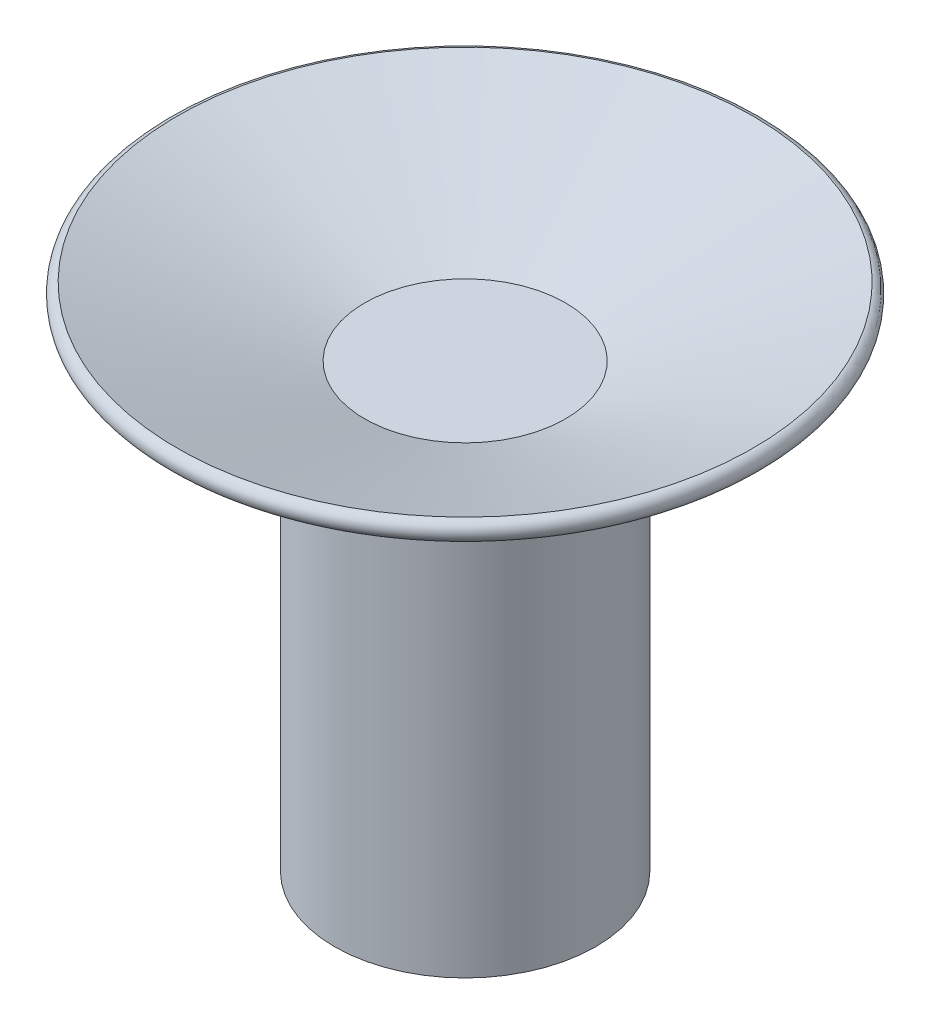
SolidWorks part; units mm, degrees
ref_plane "Plan de face" through (0, 0, 0) normal (0, 0, 1) x (1, 0, 0)
ref_plane "Plan de dessus" through (0, 0, 0) normal (0, 1, 0) x (1, 0, 0)
ref_plane "Plan de droite" through (0, 0, 0) normal (1, 0, 0) x (0, 0, -1)
sketch "Esquisse1" plane through (0, 0, 0) normal (0, 0, 1) x (1, 0, 0)
  line L0 (0, 0) -> (0, 11.1884) construction
  line L1 (0, 0) -> (5, 0)
  line L2 (5, 0) -> (14.3969, 3.4202)
  line L3 (0, 0) -> (0, 1)
  line L4 (14.3226, 4.3931) -> (5, 1)
  line L5 (5, 1) -> (0, 1)
  arc A0 (14.3969, 3.4202) -> (14.3226, 4.3931) centre (14.2237, 3.8963) ccw
  dimension "D1" = 5
  dimension "D2" = 160
  dimension "D3" = 1
  dimension "D4" = 10
revolve "Révolution1" add sketch "Esquisse1" angle 360 about L0
sketch "Esquisse2" plane through (0, 0, 0) normal (0, -1, 0) x (1, 0, 0)
  line L1 (2.7924, -4.1476) -> (4.9881, 0.3445)
  line L2 (4.9881, 0.3445) -> (2.1957, 4.4921)
  line L3 (2.1957, 4.4921) -> (-2.7924, 4.1476)
  line L4 (-2.7924, 4.1476) -> (-4.9881, -0.3445)
  line L5 (-4.9881, -0.3445) -> (-2.1957, -4.4921)
  line L6 (-2.1957, -4.4921) -> (2.7924, -4.1476)
  circle A0 centre (0, 0) radius 4.3301 construction
extrude "Boss.-Extru.1" add sketch "Esquisse2" along normal blind 1
sketch "Sketch1" plane through (0, -1, 0) normal (0, -1, 0) x (1, 0, 0)
  circle A0 centre (0, 0) radius 6.5
  dimension "D1" = 13
extrude "Boss-Extrude1" add sketch "Sketch1" along normal blind 20
